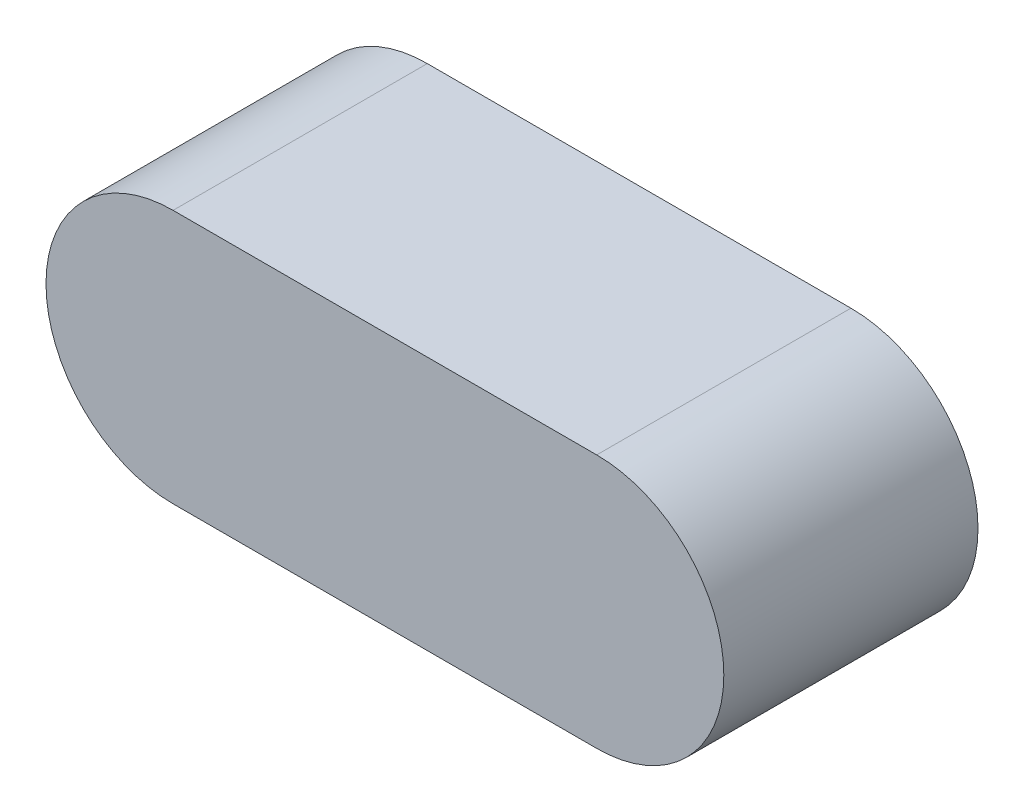
SolidWorks part; units mm, degrees
ref_plane "Front Plane" through (0, 0, 0) normal (0, 0, 1) x (1, 0, 0)
ref_plane "Top Plane" through (0, 0, 0) normal (0, 1, 0) x (1, 0, 0)
ref_plane "Right Plane" through (0, 0, 0) normal (1, 0, 0) x (0, 0, -1)
sketch "Sketch1" plane through (0, 0, 0) normal (0, 1, 0) x (1, 0, 0)
  line L0 (-6.35, 0) -> (6.35, 0) construction
  line L1 (-6.35, 2.3812) -> (6.35, 2.3812)
  line L2 (-6.35, 2.3812) -> (-6.35, -2.3813)
  line L3 (-6.35, -2.3813) -> (6.35, -2.3813)
  line L4 (6.35, 2.3812) -> (6.35, -2.3813)
  dimension "Square Size" = 4.7625
  dimension "Length" = 12.7
extrude "Extrude1" add sketch "Sketch1" against normal blind 4.7625
sketch "Sketch2" plane through (44.45, 6.35, 2.3812) normal (0, 0, -1) x (-1, 0, 0)
  line L0 (40.4812, -8.7312) -> (48.4187, -8.7312) construction
  line L1 (40.4812, -6.35) -> (48.4187, -6.35)
  line L2 (40.4812, -11.1125) -> (48.4187, -11.1125)
  line L5 (50.8, -8.7312) -> (48.4187, -8.7312) construction
  line L6 (40.4812, -8.7312) -> (38.1, -8.7312) construction
  line L7 (38.1, -11.1125) -> (38.1, -6.35) construction
  line L8 (50.8, -11.1125) -> (50.8, -6.35) construction
  line L9 (38.1, -6.35) -> (50.8, -6.35) construction
  arc A0 (40.4812, -6.35) -> (40.4812, -11.1125) centre (40.4812, -8.7312) ccw
  arc A1 (48.4187, -11.1125) -> (48.4187, -6.35) centre (48.4187, -8.7312) ccw
  point P2 (44.45, -8.7312)
extrude "Extrude2" cut sketch "Sketch2" along normal through all flip side to cut
sketch "Sketch3" plane through (0, 0, 0) normal (0, 1, 0) x (1, 0, 0)
  line L0 (0, -2.3812) -> (0, 2.3813) construction
  line L1 (-3.9688, -2.3813) -> (3.9688, -2.3812) construction
  line L2 (3.9688, 2.3812) -> (-3.9688, 2.3813) construction
  dimension "D1" = 4.7625
